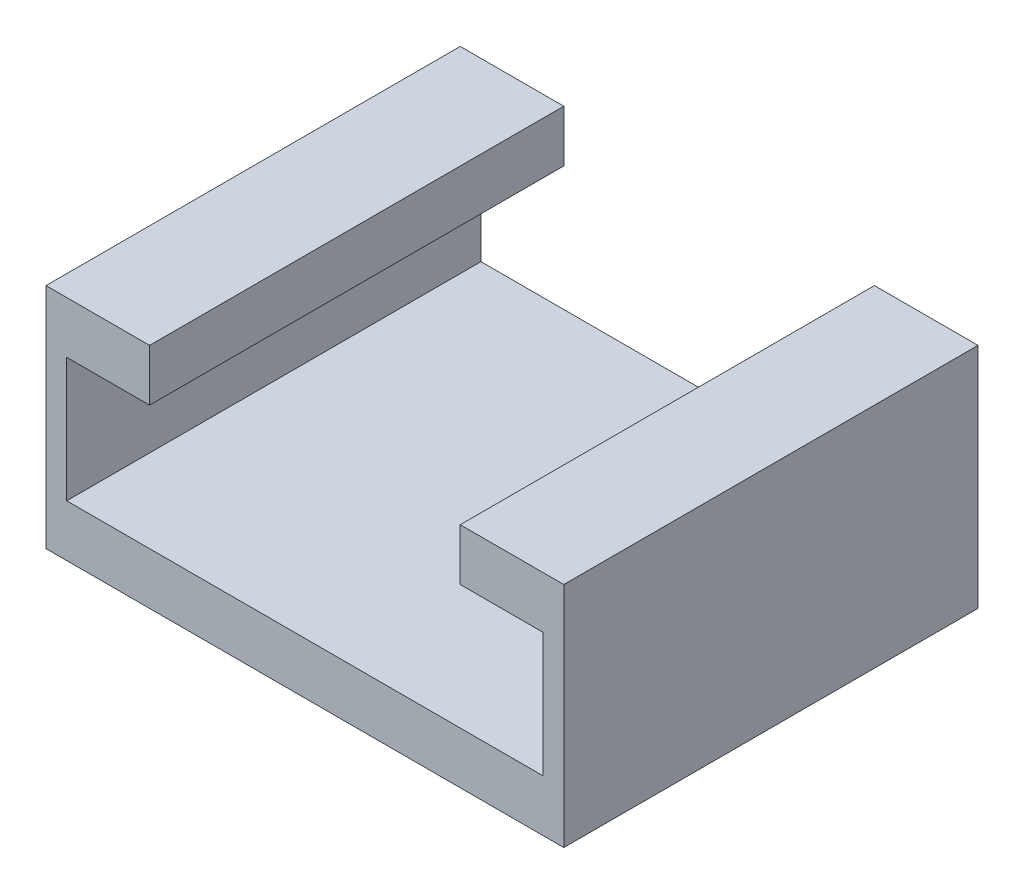
SolidWorks part; units mm, degrees
ref_plane "Front Plane" through (0, 0, 0) normal (0, 0, 1) x (1, 0, 0)
ref_plane "Top Plane" through (0, 0, 0) normal (0, 1, 0) x (1, 0, 0)
ref_plane "Right Plane" through (0, 0, 0) normal (1, 0, 0) x (0, 0, -1)
sketch "Sketch1" plane through (0, 0, 0) normal (0, 1, 0) x (1, 0, 0)
  line L1 (0, 0) -> (50, 0)
  line L2 (0, 0) -> (0, 40)
  line L3 (0, 40) -> (50, 40)
  line L4 (50, 0) -> (50, 40)
  dimension "D1" = 50
  dimension "D2" = 40
extrude "Boss-Extrude2" add sketch "Sketch1" along normal blind 5 contours L2 L3 L4 L1
sketch "Sketch2" plane through (0, 5, 0) normal (0, 1, 0) x (1, 0, 0)
  line L0 (0, 0) -> (50, 0) construction
  line L1 (0, 40) -> (2, 40)
  line L2 (0, 40) -> (0, 0)
  line L3 (0, 0) -> (2, 0)
  line L4 (2, 40) -> (2, 0)
  line L6 (50, 40) -> (48, 40)
  line L7 (50, 40) -> (50, 0)
  line L8 (50, 0) -> (48, 0)
  line L9 (48, 40) -> (48, 0)
  dimension "D1" = 2
  dimension "D2" = 2
extrude "Boss-Extrude4" add sketch "Sketch2" along normal blind 12
sketch "Sketch3" plane through (0, 17, 0) normal (0, 1, 0) x (1, 0, 0)
  line L1 (0, 40) -> (10, 40)
  line L2 (0, 40) -> (0, 0)
  line L3 (0, 0) -> (10, 0)
  line L4 (10, 40) -> (10, 0)
  line L5 (50, 40) -> (40, 40)
  line L6 (50, 40) -> (50, 0)
  line L7 (50, 0) -> (40, 0)
  line L8 (40, 40) -> (40, 0)
  dimension "D1" = 10
  dimension "D2" = 10
extrude "Boss-Extrude5" add sketch "Sketch3" along normal blind 5
ref_plane "Plane1" through (0, 0, -35) normal (0, 0, 1) x (1, 0, 0)
ref_plane "Plane2" through (25, 0, 0) normal (1, 0, 0) x (0, 0, -1)
sketch "Sketch5" plane through (25, 0, 0) normal (1, 0, 0) x (0, 0, -1)
  line L0 (0, 0) -> (40, 0) construction
  line L2 (23.5, 0) -> (28.5, 0)
  line L3 (23.5, 0) -> (23.5, -2.5)
  line L5 (28.5, 0) -> (28.5, -2.5)
  circle A0 centre (26, -2) radius 1.5
  arc A1 (23.5, -2.5) -> (28.5, -2.5) centre (26, -2.5) ccw
  dimension "D1" = 3
  dimension "D2" = 14
  dimension "D3" = 2
  dimension "D4" = 5
  dimension "D5" = 2.5
  dimension "D6" = 2.5
extrude "Boss-Extrude6" add sketch "Sketch5" along normal blind 15 and the other way blind 15 contours L3 A1 L5 L2 A0
